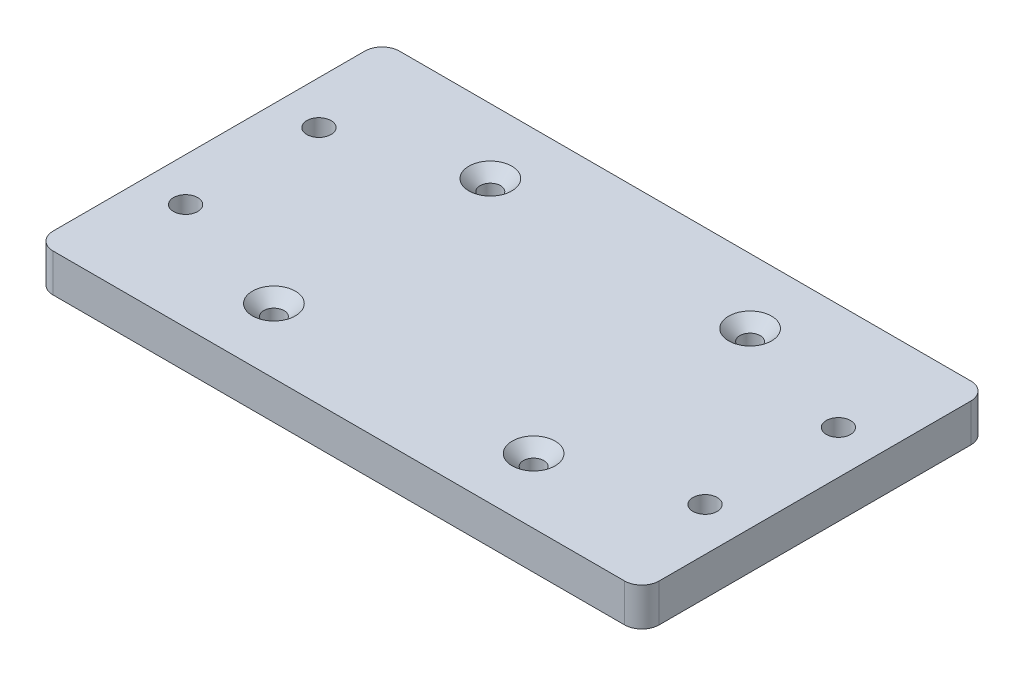
SolidWorks part; units mm, degrees
ref_plane "Front Plane" through (0, 0, 0) normal (0, 0, 1) x (1, 0, 0)
ref_plane "Top Plane" through (0, 0, 0) normal (0, 1, 0) x (1, 0, 0)
ref_plane "Right Plane" through (0, 0, 0) normal (1, 0, 0) x (0, 0, -1)
sketch "Sketch1" plane through (0, 0, 0) normal (0, 1, 0) x (1, 0, 0)
  line L1 (-44.45, 25.4) -> (44.45, 25.4)
  line L2 (-44.45, 25.4) -> (-44.45, -25.4)
  line L3 (-44.45, -25.4) -> (44.45, -25.4)
  line L4 (44.45, 25.4) -> (44.45, -25.4)
  line L5 (-44.45, 25.4) -> (44.45, -25.4) construction
  line L6 (-44.45, -25.4) -> (44.45, 25.4) construction
  point P0 (0, 0)
  dimension "D1" = 88.9
  dimension "D2" = 50.8
extrude "Boss-Extrude1" add sketch "Sketch1" along normal blind 5.588
sketch "Sketch2" plane through (0, 5.588, 0) normal (0, 1, 0) x (1, 0, 0)
  line L0 (0, -25.4) -> (0, 25.4) construction
  line L1 (-44.45, -25.4) -> (44.45, -25.4) construction
  line L2 (44.45, 25.4) -> (-44.45, 25.4) construction
  line L3 (44.45, 0) -> (-44.45, 0) construction
  line L4 (44.45, -25.4) -> (44.45, 25.4) construction
  line L5 (-44.45, 25.4) -> (-44.45, -25.4) construction
  line L6 (-38.1, -9.779) -> (-38.1, 9.779) construction
  line L7 (-19.05, -15.875) -> (-19.05, 15.875) construction
  circle A0 centre (-38.1, -9.779) radius 1.778
  circle A1 centre (-38.1, 9.779) radius 1.778
  circle A4 centre (-19.05, -15.875) radius 1.5
  circle A5 centre (-19.05, 15.875) radius 1.5
  point P19 (-38.1, 0)
  point P20 (-19.05, 0)
  dimension "D2" = 3.556
  dimension "D4" = 31.75
  dimension "D6" = 3
  dimension "D1" = 38.1
  dimension "D3" = 19.558
  dimension "D5" = 19.05
extrude "Cut-Extrude1" cut sketch "Sketch2" against normal up to next
mirror "Mirror1" about plane through (0, 0, 0) normal (1, 0, 0) of "Cut-Extrude1"
fillet "Fillet1" radius 2.54 4 edges at (44.45, 2.794, 25.4) (-44.45, 2.794, 25.4) (-44.45, 2.794, -25.4) (44.45, 2.794, -25.4)
chamfer "Chamfer1" distance 1.65 angle 45 4 edges at (19.05, 5.588, -14.375) (-19.05, 5.588, -14.375) (-19.05, 5.588, 17.375) (19.05, 5.588, 17.375)
